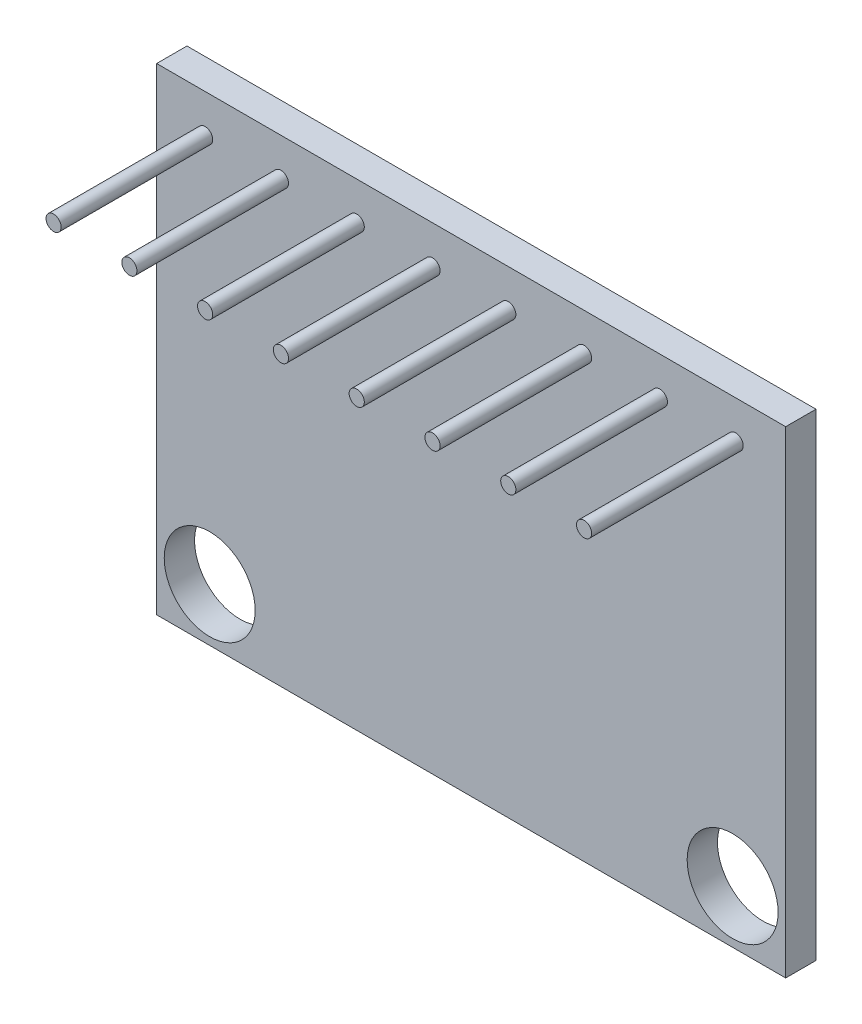
SolidWorks part; units mm, degrees
ref_plane "Plan de face" through (0, 0, 0) normal (0, 0, 1) x (1, 0, 0)
ref_plane "Plan de dessus" through (0, 0, 0) normal (0, 1, 0) x (1, 0, 0)
ref_plane "Plan de droite" through (0, 0, 0) normal (1, 0, 0) x (0, 0, -1)
sketch "Esquisse1" plane through (0, 0, 0) normal (0, 0, 1) x (1, 0, 0)
  line L1 (0, 0) -> (-20.75, 0)
  line L2 (0, 0) -> (0, 15.75)
  line L3 (0, 15.75) -> (-20.75, 15.75)
  line L4 (-20.75, 0) -> (-20.75, 15.75)
  dimension "D1" = 20.75
  dimension "D2" = 15.75
extrude "Boss.-Extru.1" add sketch "Esquisse1" along normal blind 1
sketch "Esquisse4" plane through (0, 0, 0) normal (0, 0, -1) x (-1, 0, 0)
  line L0 (0, 7.875) -> (20.75, 7.875) construction
  line L1 (0, 0) -> (0, 15.75) construction
  line L2 (20.75, 15.75) -> (20.75, 0) construction
  line L3 (8.375, 7.875) -> (12.375, 7.875) construction
  line L4 (4.375, 9.875) -> (4.875, 9.875)
  line L5 (4.375, 9.875) -> (4.375, 7.875)
  line L6 (4.375, 7.875) -> (4.875, 7.875)
  line L7 (4.875, 9.875) -> (4.875, 7.875)
  line L8 (5.375, 9.875) -> (5.875, 9.875)
  line L9 (5.375, 9.875) -> (5.375, 8.875)
  line L10 (5.375, 8.875) -> (5.875, 8.875)
  line L11 (5.875, 9.875) -> (5.875, 8.875)
  line L12 (6.375, 9.875) -> (6.875, 9.875)
  line L13 (6.375, 9.875) -> (6.375, 7.875)
  line L14 (6.375, 7.875) -> (6.875, 7.875)
  line L15 (6.875, 9.875) -> (6.875, 7.875)
  line L16 (13.875, 9.875) -> (14.375, 9.875)
  line L17 (13.875, 9.875) -> (13.875, 7.875)
  line L18 (13.875, 7.875) -> (14.375, 7.875)
  line L19 (14.375, 9.875) -> (14.375, 7.875)
  line L20 (14.875, 9.875) -> (15.375, 9.875)
  line L21 (14.875, 9.875) -> (14.875, 8.875)
  line L22 (14.875, 8.875) -> (15.375, 8.875)
  line L23 (15.375, 9.875) -> (15.375, 8.875)
  line L24 (15.875, 9.875) -> (16.375, 9.875)
  line L25 (15.875, 9.875) -> (15.875, 7.875)
  line L26 (15.875, 7.875) -> (16.375, 7.875)
  line L27 (16.375, 9.875) -> (16.375, 7.875)
  line L28 (8.375, 9.875) -> (12.375, 9.875)
  line L29 (8.375, 9.875) -> (8.375, 5.875)
  line L30 (8.375, 5.875) -> (12.375, 5.875)
  line L31 (12.375, 9.875) -> (12.375, 5.875)
  line L32 (4.375, 6.875) -> (4.875, 6.875)
  line L33 (4.375, 6.875) -> (4.375, 5.875)
  line L34 (4.375, 5.875) -> (4.875, 5.875)
  line L35 (4.875, 6.875) -> (4.875, 5.875)
  line L36 (6.375, 6.875) -> (6.875, 6.875)
  line L37 (6.375, 6.875) -> (6.375, 4.875)
  line L38 (6.375, 4.875) -> (6.875, 4.875)
  line L39 (6.875, 6.875) -> (6.875, 4.875)
  line L40 (8.7567, 4.0741) -> (11.2567, 4.0741)
  line L41 (8.7567, 4.0741) -> (8.7567, 3.0741)
  line L42 (8.7567, 3.0741) -> (11.2567, 3.0741)
  line L43 (11.2567, 4.0741) -> (11.2567, 3.0741)
  line L44 (13.875, 6.875) -> (14.375, 6.875)
  line L45 (13.875, 6.875) -> (13.875, 5.875)
  line L46 (13.875, 5.875) -> (14.375, 5.875)
  line L47 (14.375, 6.875) -> (14.375, 5.875)
  line L48 (15.875, 6.875) -> (16.375, 6.875)
  line L49 (15.875, 6.875) -> (15.875, 4.875)
  line L50 (15.875, 4.875) -> (16.375, 4.875)
  line L51 (16.375, 6.875) -> (16.375, 4.875)
  line L52 (2, 2) -> (2, 0) construction
  line L53 (20.75, 0) -> (0, 0) construction
  line L54 (2, 2) -> (0, 2) construction
  line L55 (18.75, 2) -> (20.75, 2) construction
  line L56 (18.75, 2) -> (18.75, 0) construction
  circle A0 centre (2, 2) radius 1.5
  circle A1 centre (18.75, 2) radius 1.5
  point P60 (10.375, 7.875)
  point P61 (10.375, 7.875)
  point P62 (10.375, 7.9577)
  point P63 (10.375, 7.9577)
  dimension "D45" = 3
  dimension "D46" = 3
  dimension "D1" = 0.5
  dimension "D2" = 0.5
  dimension "D3" = 0.5
  dimension "D4" = 0.5
  dimension "D5" = 0.5
  dimension "D6" = 0.5
  dimension "D7" = 0.5
  dimension "D8" = 0.5
  dimension "D9" = 0.5
  dimension "D10" = 0.5
  dimension "D11" = 1.5
  dimension "D12" = 1.5
  dimension "D13" = 4
  dimension "D14" = 4
  dimension "D15" = 0
  dimension "D16" = 0
  dimension "D17" = 0
  dimension "D18" = 0
  dimension "D19" = 2
  dimension "D20" = 1
  dimension "D21" = 2
  dimension "D22" = 2
  dimension "D23" = 1
  dimension "D24" = 2
  dimension "D25" = 0
  dimension "D26" = 0
  dimension "D27" = 0
  dimension "D28" = 0
  dimension "D29" = 0.5
  dimension "D30" = 2
  dimension "D31" = 1
  dimension "D32" = 0.5
  dimension "D33" = 0.5
  dimension "D34" = 0.5
  dimension "D35" = 0
  dimension "D36" = 0
  dimension "D37" = 1
  dimension "D38" = 2
  dimension "D39" = 1
  dimension "D40" = 1
  dimension "D41" = 1
  dimension "D42" = 1
  dimension "D43" = 2.5
  dimension "D44" = 1
  dimension "D47" = 2
  dimension "D48" = 2
  dimension "D49" = 2
  dimension "D50" = 2
extrude "Boss.-Extru.4" add sketch "Esquisse4" along normal blind 0.5 contours L15 L12 L13 L14 | L11 L8 L9 L10 | L7 L4 L5 L6 | L35 L32 L33 L34 | L39 L36 L37 L38 | L43 L40 L41 L42 | L29 L28 L31 L30 | L17 L16 L19 L18 | L25 L24 L27 L26 | L21 L20 L23 L22 | L45 L44 L47 L46 | L49 L48 L51 L50
sketch "Esquisse5" plane through (0, 0, 0) normal (0, 0, -1) x (-1, 0, 0)
  line L0 (0, 3.5) -> (20.75, 3.5) construction
  line L1 (0, 0) -> (0, 15.75) construction
  line L2 (20.75, 15.75) -> (20.75, 0) construction
  line L3 (20.75, 3.5) -> (20.75, 0) construction
  line L4 (20.75, 0) -> (0, 0) construction
  line L5 (20.75, 0) -> (17.25, 0) construction
  line L6 (17.25, 0) -> (3.5, 0) construction
  line L7 (3.5, 0) -> (0, 0) construction
  line L8 (0, 0) -> (0, 3.5) construction
  line L9 (17.25, 0) -> (20.75, 3.5) construction
  line L10 (0, 3.5) -> (3.5, 0) construction
  circle A0 centre (1.75, 1.75) radius 1.5
  circle A1 centre (19, 1.75) radius 1.5
  dimension "D4" = 3
  dimension "D5" = 3
  dimension "D1" = 3.5
  dimension "D2" = 3.5
  dimension "D3" = 3.5
extrude "Enlèv. mat.-Extru.1" cut sketch "Esquisse5" against normal blind 5
sketch "Esquisse6" plane through (0, 0, 0) normal (0, 0, -1) x (-1, 0, 0)
  line L0 (15.875, 9.875) -> (16.375, 9.875) construction
  line L1 (17.75, 9.875) -> (20.25, 9.875)
  line L2 (17.75, 9.875) -> (17.75, 7.875)
  line L3 (17.75, 7.875) -> (20.25, 7.875)
  line L4 (20.25, 9.875) -> (20.25, 7.875)
  line L5 (20.75, 15.75) -> (20.75, 0) construction
  dimension "D1" = 2.5
  dimension "D2" = 2
  dimension "D3" = 0
  dimension "D4" = 0.5
extrude "Boss.-Extru.5" add sketch "Esquisse6" along normal blind 0.5
sketch "Esquisse7" plane through (0, 0, 1) normal (0, 0, 1) x (1, 0, 0)
  line L0 (-20.75, 14.5) -> (-19.15, 14.5) construction
  line L1 (-20.75, 15.75) -> (-20.75, 0) construction
  line L2 (-19.15, 14.5) -> (-1.6, 14.5) construction
  line L3 (-1.6, 14.5) -> (0, 14.5) construction
  line L4 (0, 0) -> (0, 15.75) construction
  line L5 (0, 15.75) -> (-20.75, 15.75) construction
  circle A0 centre (-19.15, 14.5) radius 0.25
  circle A1 centre (-16.65, 14.5) radius 0.25
  circle A2 centre (-14.15, 14.5) radius 0.25
  circle A3 centre (-11.65, 14.5) radius 0.25
  circle A4 centre (-9.15, 14.5) radius 0.25
  circle A5 centre (-6.65, 14.5) radius 0.25
  circle A6 centre (-4.15, 14.5) radius 0.25
  circle A7 centre (-1.65, 14.5) radius 0.25
  dimension "D4" = 0.5
  dimension "D1" = 1.6
  dimension "D2" = 1.6
  dimension "D3" = 1.25
  dimension "D5" = 8
extrude "Boss.-Extru.6" add sketch "Esquisse7" along normal blind 5 and the other way blind 1.5
